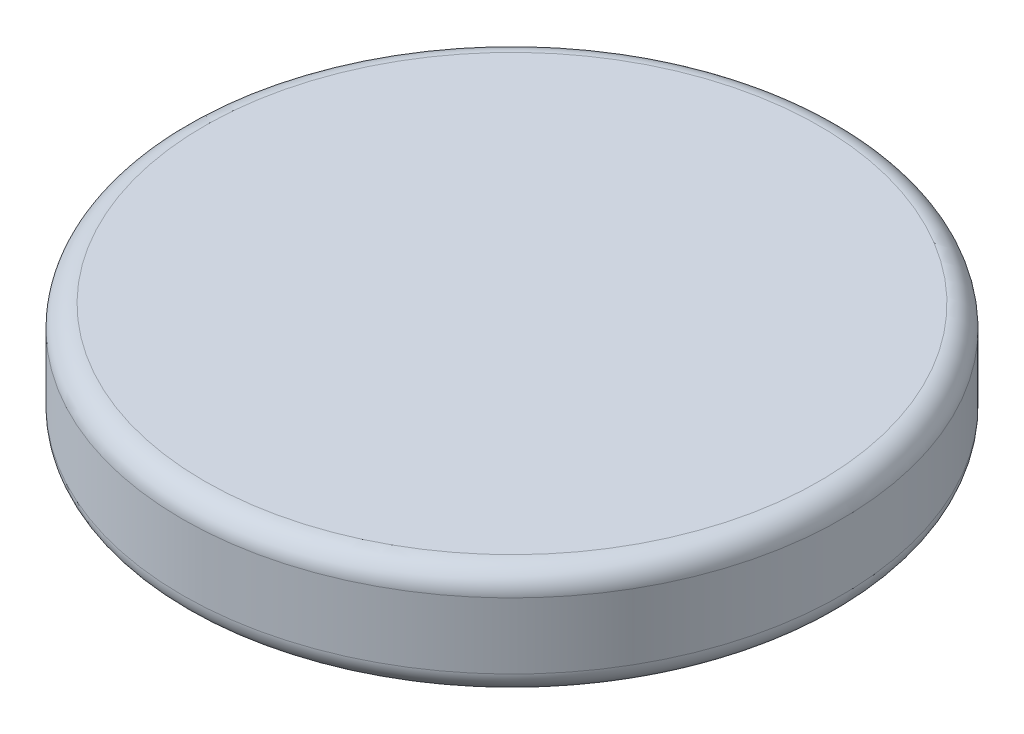
SolidWorks part; units mm, degrees
ref_plane "Front Plane" through (0, 0, 0) normal (0, 0, 1) x (1, 0, 0)
ref_plane "Top Plane" through (0, 0, 0) normal (0, 1, 0) x (1, 0, 0)
ref_plane "Right Plane" through (0, 0, 0) normal (1, 0, 0) x (0, 0, -1)
sketch "Sketch1" plane through (0, 0, 0) normal (0, 1, 0) x (1, 0, 0)
  circle A0 centre (0, 0) radius 15
  dimension "D1" = 30
extrude "Boss-Extrude1" add sketch "Sketch1" along normal blind 5
fillet "Fillet1" radius 1 2 edges at (0, 0, 15) (0, 5, 15)
